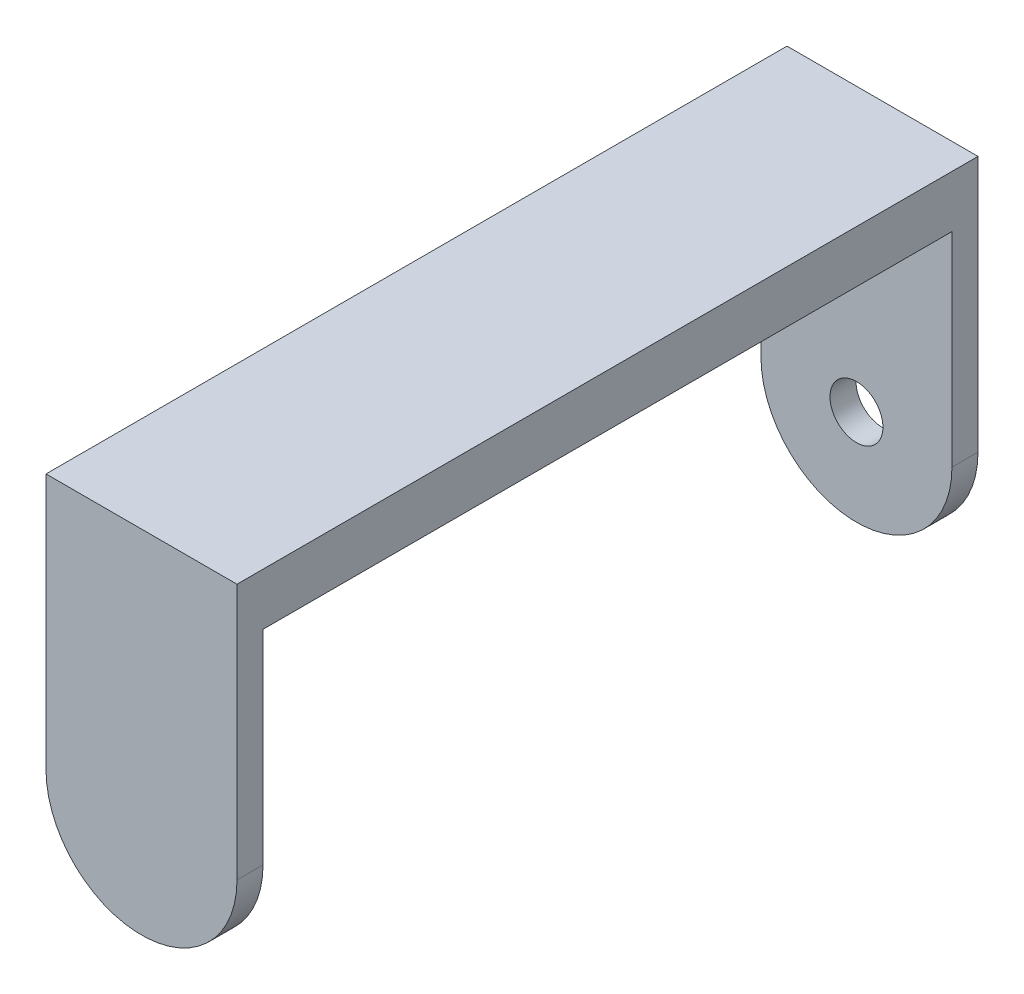
SolidWorks part; units mm, degrees
ref_plane "Plano frontal" through (0, 0, 0) normal (0, 0, 1) x (1, 0, 0)
ref_plane "Plano superior" through (0, 0, 0) normal (0, 1, 0) x (1, 0, 0)
ref_plane "Plano direito" through (0, 0, 0) normal (1, 0, 0) x (0, 0, -1)
sketch "Esboço1" plane through (0, 0, 0) normal (0, 0, 1) x (1, 0, 0)
  line L0 (11, -1.4281) -> (11, 25.0719)
  line L1 (11, 25.0719) -> (-11, 25.0719)
  line L2 (-11, 25.0719) -> (-11, -1.4281)
  line L4 (11, -3.4281) -> (11, 5.0719) construction
  line L5 (7.3, 10.0719) -> (-7.3, 10.0719) construction
  circle A3 centre (0, -1.4281) radius 11 construction
  arc A8 (-11, -1.4281) -> (11, -1.4281) centre (0, -1.4281) ccw
  circle A9 centre (0, -1.4281) radius 3.05 construction
  circle A10 centre (0, -1.4281) radius 3.05
  dimension "D1" = 15
extrude "Ressalto-extrusão1" add sketch "Esboço1" against normal blind 3
sketch "Esboço2" plane through (0, 25.0719, 0) normal (0, 1, 0) x (1, 0, 0)
  line L0 (-3.85, -78.5) -> (3.85, -78.5) construction
  line L1 (-11, 3) -> (11, 3)
  line L2 (-11, 3) -> (-11, -79.35)
  line L3 (-11, -79.35) -> (11, -79.35)
  line L4 (11, 3) -> (11, -79.35)
  dimension "D1" = 0.85
extrude "Ressalto-extrusão2" add sketch "Esboço2" along normal blind 3
sketch "Esboço3" plane through (0, 0, 79.35) normal (0, 0, 1) x (1, 0, 0)
  line L0 (11, 28.0719) -> (-11, 28.0719)
  line L1 (-11, 28.0719) -> (-11, -1.4281)
  line L2 (11, -1.4281) -> (11, 28.0719)
  arc A0 (-11, -1.4281) -> (11, -1.4281) centre (0, -1.4281) ccw
  circle A3 centre (0, -1.4281) radius 4 construction
extrude "Ressalto-extrusão3" add sketch "Esboço3" along normal blind 3
sketch "Esboço6" plane through (11, 0, 0) normal (1, 0, 0) x (0, 0, -1)
  line L0 (3, -1.4281) -> (3, 28.0719) construction
  line L1 (-82.35, 28.0719) -> (3, 28.0719)
  line L2 (-82.35, 28.0719) -> (-82.35, 22.0719)
  line L3 (-82.35, 22.0719) -> (3, 22.0719)
  line L4 (3, 28.0719) -> (3, 22.0719)
  line L5 (-79.35, 25.0719) -> (0, 25.0719) construction
  dimension "D1" = 3
extrude "Ressalto-extrusão5" add sketch "Esboço6" against normal blind 3
mirror "Espelhar1" about plane through (0, 0, 0) normal (1, 0, 0) of "Ressalto-extrusão5"
sketch "Esboço7" plane through (0, 0, 79.35) normal (0, 0, -1) x (-1, 0, 0)
  circle A0 centre (0, -1.4281) radius 2.75
  circle A2 centre (0, -1.4281) radius 3.25 construction
  dimension "D1" = 0.5
extrude "Ressalto-extrusão6" add sketch "Esboço7" along normal offset from surface (0.6 mm away) 0.25
